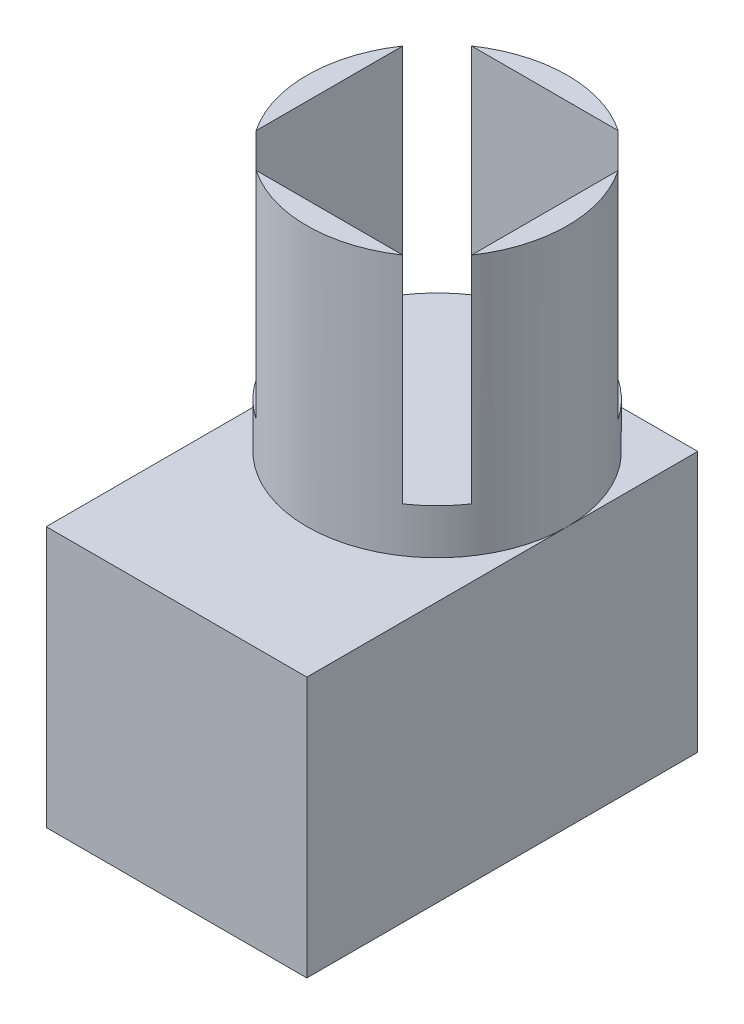
SolidWorks part; units mm, degrees
ref_plane "Front Plane" through (0, 0, 0) normal (0, 0, 1) x (1, 0, 0)
ref_plane "Top Plane" through (0, 0, 0) normal (0, 1, 0) x (1, 0, 0)
ref_plane "Right Plane" through (0, 0, 0) normal (1, 0, 0) x (0, 0, -1)
sketch "Sketch1" plane through (0, 0, 0) normal (0, 1, 0) x (1, 0, 0)
  circle A0 centre (0, 0) radius 25.4
  dimension "D1" = 50.8
extrude "Boss-Extrude1" add sketch "Sketch1" along normal blind 101.6
sketch "Sketch2" plane through (0, 101.6, 0) normal (0, 1, 0) x (1, 0, 0)
  line L1 (-21.0058, -21.0058) -> (21.0058, -21.0058)
  line L2 (-21.0058, -21.0058) -> (-21.0058, 21.0058)
  line L3 (-21.0058, 21.0058) -> (21.0058, 21.0058)
  line L4 (21.0058, -21.0058) -> (21.0058, 21.0058)
  line L5 (-21.0058, -21.0058) -> (21.0058, 21.0058) construction
  line L6 (-21.0058, 21.0058) -> (21.0058, -21.0058) construction
  point P0 (0, 0)
  dimension "D1" = 42.0116
extrude "Cut-Extrude1" cut sketch "Sketch2" against normal blind 42.0116
sketch "Sketch3" plane through (0, 0, 0) normal (0, -1, 0) x (1, 0, 0)
  line L1 (-25.4, -25.4) -> (25.4, -25.4)
  line L2 (-25.4, -25.4) -> (-25.4, 50.8)
  line L3 (-25.4, 50.8) -> (25.4, 50.8)
  line L4 (25.4, -25.4) -> (25.4, 50.8)
  circle A0 centre (0, 0) radius 25.4 construction
  dimension "D1" = 76.2
extrude "Boss-Extrude2" add sketch "Sketch3" against normal blind 50.8
sketch "Sketch4" plane through (0, 0, 0) normal (0, -1, 0) x (1, 0, 0)
  line L0 (-25.4, 50.8) -> (-25.4, -25.4) construction
  line L1 (-21.59, 46.99) -> (21.59, 46.99)
  line L2 (-21.59, 46.99) -> (-21.59, -21.59)
  line L3 (-21.59, -21.59) -> (21.59, -21.59)
  line L4 (21.59, 46.99) -> (21.59, -21.59)
  line L5 (25.4, -25.4) -> (25.4, 50.8) construction
  line L6 (25.4, 50.8) -> (-25.4, 50.8) construction
  line L7 (-25.4, -25.4) -> (25.4, -25.4) construction
  dimension "D1" = 3.81
  dimension "D2" = 3.81
  dimension "D3" = 3.81
  dimension "D4" = 3.81
extrude "Cut-Extrude2" cut sketch "Sketch4" against normal blind 44.45
sketch "Sketch5" plane through (-25.4, 0, 0) normal (-1, 0, 0) x (0, 0, 1)
  line L0 (-25.4, 50.8) -> (-25.4, 0) construction
  line L1 (-15.24, 5.08) -> (-5.842, 5.08)
  line L2 (-15.24, 5.08) -> (-15.24, 16.51)
  line L3 (-15.24, 16.51) -> (-5.842, 16.51)
  line L4 (-5.842, 5.08) -> (-5.842, 16.51)
  line L5 (50.8, 0) -> (-25.4, 0) construction
  dimension "D1" = 10.16
  dimension "D2" = 5.08
  dimension "D3" = 11.43
  dimension "D4" = 9.398
extrude "Cut-Extrude3" cut sketch "Sketch5" against normal up to next
